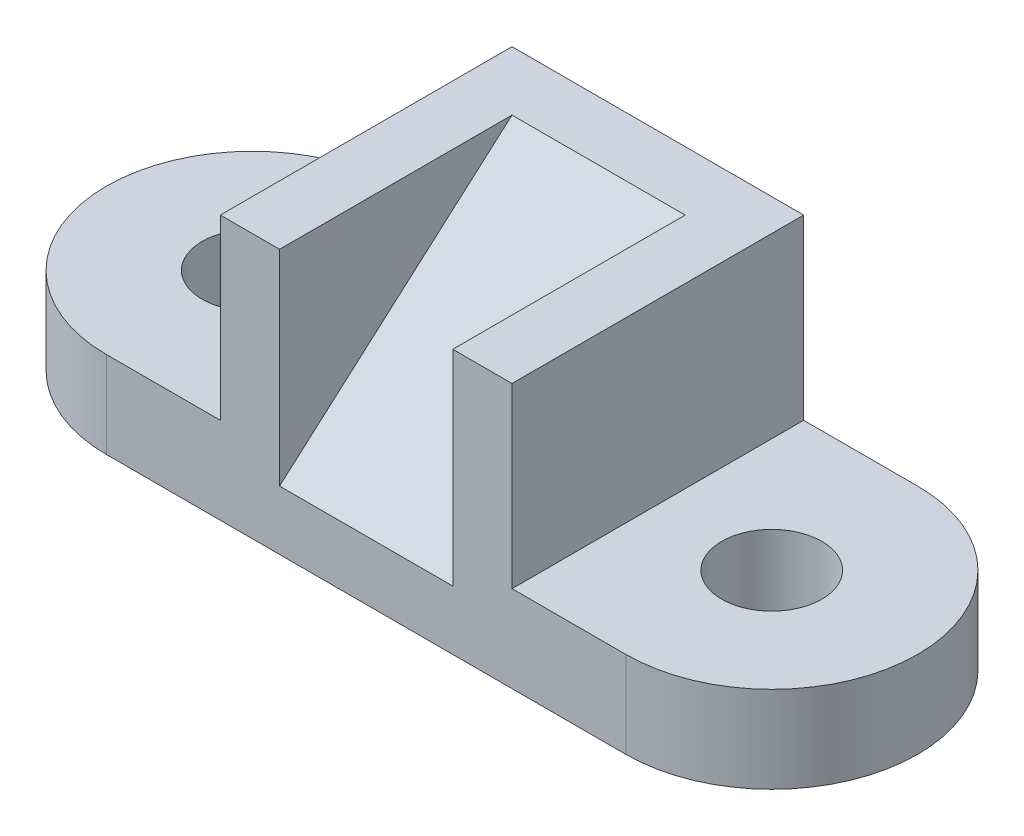
SolidWorks part; units mm, degrees
ref_plane "Front Plane" through (0, 0, 0) normal (0, 0, 1) x (1, 0, 0)
ref_plane "Top Plane" through (0, 0, 0) normal (0, 1, 0) x (1, 0, 0)
ref_plane "Right Plane" through (0, 0, 0) normal (1, 0, 0) x (0, 0, -1)
sketch "Sketch1" plane through (0, 0, 0) normal (0, 1, 0) x (1, 0, 0)
  line L0 (-57, 0) -> (57, 0) construction
  line L1 (-57, 32) -> (57, 32)
  line L2 (-57, -32) -> (57, -32)
  arc A0 (-57, 32) -> (-57, -32) centre (-57, 0) ccw
  arc A1 (57, -32) -> (57, 32) centre (57, 0) ccw
  circle A2 centre (-57, 0) radius 11
  circle A3 centre (57, 0) radius 11
  point P2 (0, 0)
  dimension "D2" = 32
  dimension "D3" = 22
  dimension "D4" = 22
  dimension "D1" = 114
extrude "Boss-Extrude1" add sketch "Sketch1" along normal blind 13
sketch "Sketch2" plane through (0, 13, 0) normal (0, 1, 0) x (1, 0, 0)
  line L0 (-57, -32) -> (57, -32) construction
  line L2 (-19, 19) -> (-19, -32)
  line L3 (-19, -32) -> (19, -32)
  line L4 (19, 19) -> (19, -32)
  line L5 (-11.2812, 19) -> (19, -32) construction
  line L6 (-19, -32) -> (11.2813, 19) construction
  line L7 (-19, 19) -> (19, 19)
  point P0 (0, 0)
  dimension "D1" = 38
extrude "Boss-Extrude3" add sketch "Sketch2" along normal blind 45
sketch "Sketch3" plane through (-19, 0, 0) normal (-1, 0, 0) x (0, 0, 1)
  line L0 (-19, 58) -> (32, 13)
extrude "Cut-Extrude1" cut sketch "Sketch3" against normal through all and the other way through all
sketch "Sketch4" plane through (0, 13, 0) normal (0, 1, 0) x (1, 0, 0)
  line L0 (-38.8197, 3.235) -> (-38.8197, -6.2678)
  line L1 (-57, -32) -> (-19, -32) construction
  line L2 (19, -32) -> (57, -32) construction
  line L3 (57, 32) -> (-57, 32) construction
  line L4 (-57, -32) -> (-19, -32)
  line L5 (19, -32) -> (57, -32)
  line L6 (57, 32) -> (-57, 32)
  arc A0 (-57, 32) -> (-57, -32) centre (-57, 0) ccw construction
  arc A1 (57, -32) -> (57, 32) centre (57, 0) ccw construction
  circle A2 centre (57, 0) radius 11 construction
  circle A3 centre (-57, 0) radius 11 construction
  arc A4 (-57, 32) -> (-57, -32) centre (-57, 0) ccw
  arc A5 (57, -32) -> (57, 32) centre (57, 0) ccw
  circle A6 centre (57, 0) radius 11
  circle A7 centre (-57, 0) radius 11
extrude "Boss-Extrude4" add sketch "Sketch4" along normal blind 6
sketch "Sketch5" plane through (0, 19, 0) normal (0, 1, 0) x (1, 0, 0)
  line L0 (19, -32) -> (57, -32) construction
  line L1 (-32, 32) -> (32, 32)
  line L2 (-32, 32) -> (-32, -32)
  line L4 (32, 32) -> (32, -32)
  line L5 (-32, 32) -> (32, -32) construction
  line L6 (-32, -32) -> (32, 32) construction
  line L7 (-19, 19) -> (-19, -25.2) construction
  line L8 (19, 19) -> (19, -25.2) construction
  line L9 (-57, -32) -> (-19, -32) construction
  line L10 (19, -25.2) -> (19, -32) construction
  line L11 (19, 19) -> (-19, 19) construction
  line L12 (-19, -25.2) -> (-19, 19) construction
  line L13 (-19, -25.2) -> (-19, -32) construction
  line L14 (-32, -32) -> (-19, -32)
  line L15 (19, -32) -> (32, -32)
  line L16 (19, -25.2) -> (19, -32)
  line L17 (19, 19) -> (19, -25.2)
  line L18 (19, 19) -> (-19, 19)
  line L19 (-19, -25.2) -> (-19, 19)
  line L20 (-19, -25.2) -> (-19, -32)
  point P0 (0, 0)
  dimension "D1" = 64
  dimension "D2" = 13
  dimension "D3" = 13
  dimension "D4" = 38
  dimension "D5" = 64
  dimension "D6" = 13
extrude "Boss-Extrude5" add sketch "Sketch5" along normal blind 39
